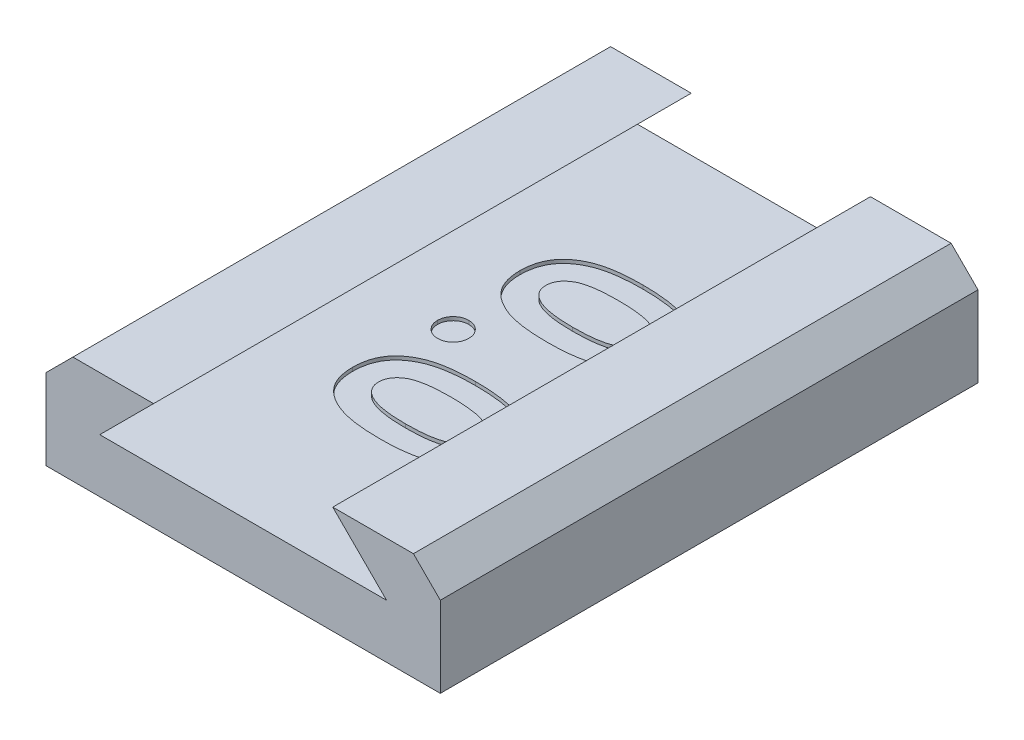
SolidWorks part; units mm, degrees
ref_plane "Front Plane" through (0, 0, 0) normal (0, 0, 1) x (1, 0, 0)
ref_plane "Top Plane" through (0, 0, 0) normal (0, 1, 0) x (1, 0, 0)
ref_plane "Right Plane" through (0, 0, 0) normal (1, 0, 0) x (0, 0, -1)
sketch "Sketch2" plane through (0, 0, 0) normal (0, 0, 1) x (1, 0, 0)
  line L0 (-11, 0) -> (11, 0)
  line L1 (11, 0) -> (11, 4.5)
  line L2 (11, 4.5) -> (9.5, 6)
  line L3 (9.5, 6) -> (5, 6)
  line L4 (5, 6) -> (8, 3)
  line L5 (8, 3) -> (-8, 3)
  line L6 (-8, 3) -> (-5, 6)
  line L7 (-5, 6) -> (-9.5, 6)
  line L8 (-9.5, 6) -> (-11, 4.5)
  line L9 (-11, 4.5) -> (-11, 0)
  point P0 (0, 0)
  point P10 (-11.3359, -3.0612)
  point P12 (0, 3)
  point P14 (5.5702, 9.8719)
  point P15 (-4.799, 7.4127)
  point P16 (-5, 8.1542)
  point P17 (-11, 0)
  point P18 (-5, 6.1755)
  dimension "D1" = 16
  dimension "D2" = 45
  dimension "D3" = 3
  dimension "D4" = 45
  dimension "D5" = 22
  dimension "D6" = 1.5
  dimension "D7" = 1.5
  dimension "D8" = 3
extrude "Boss-Extrude1" add sketch "Sketch2" along normal blind 30
sketch "Sketch3" plane through (0, 3, 0) normal (0, 1, 0) x (1, 0, 0)
  line L0 (-4, 0) -> (-4, -30) construction
  line L1 (8, 0) -> (-8, 0) construction
  line L2 (8, -30) -> (-8, -30) construction
  text T0 "0.0" font "Century Gothic" height 8
  point P6 (-4.3377, 0)
  dimension "D1" = 1
extrude "Cut-Extrude1" cut sketch "Sketch3" against normal blind 0.2
